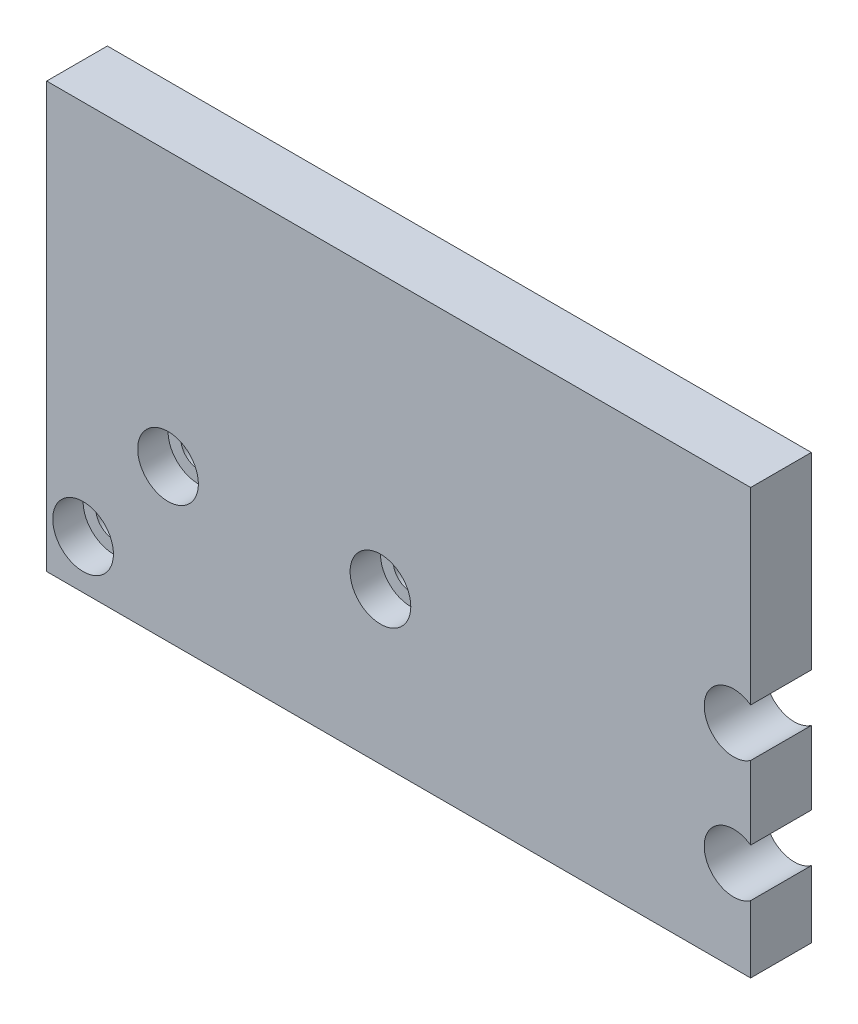
SolidWorks part; units mm, degrees
material "SKD11淬火HRC56-60"
ref_plane "前基準面" through (0, 0, 0) normal (0, 0, 1) x (1, 0, 0)
ref_plane "上基準面" through (0, 0, 0) normal (0, 1, 0) x (1, 0, 0)
ref_plane "右基準面" through (0, 0, 0) normal (1, 0, 0) x (0, 0, -1)
sketch "草图1" plane through (0, 0, 0) normal (0, 0, 1) x (1, 0, 0)
  line L1 (0, 0) -> (116, 0)
  line L2 (0, 0) -> (0, 70)
  line L3 (0, 70) -> (116, 70)
  line L4 (116, 0) -> (116, 70)
  dimension "D1" = 116
  dimension "D2" = 70
extrude "凸台-拉伸1" add sketch "草图1" along normal blind 10
sketch "草图2" plane through (0, 0, 10) normal (0, 0, 1) x (1, 0, 0)
  line L0 (0, 0) -> (116, 0) construction
  line L1 (116, 0) -> (116, 70) construction
  circle A0 centre (113.2, 35) radius 4.85
  circle A1 centre (113.2, 15) radius 4.85
  dimension "D1" = 15
  dimension "D2" = 9.7
  dimension "D3" = 20
  dimension "D4" = 2.8
extrude "切除-拉伸1" cut sketch "草图2" against normal through all
hole_wizard "M5 六角凹头螺钉的柱形沉头孔1" positions "草图5" profile "草图4" counterbore size "M5" standard "ISO" end condition through all
sketch "草图5" plane through (0, 0, 10) normal (0, 0, 1) x (1, 0, 0)
  line L0 (0, 0) -> (116, 0) construction
  line L1 (0, 70) -> (0, 0) construction
  point P0 (6, 8)
  point P1 (20, 25)
  point P3 (55, 25)
  dimension "D1" = 8
  dimension "D2" = 6
  dimension "D3" = 35
  dimension "D4" = 20
  dimension "D5" = 25
sketch "草图4" plane through (6, 8, 10) normal (1, 0, 0) x (0, -1, 0)
  line L0 (0, 0) -> (0, 10)
  line L1 (0, 10) -> (2.9, 10)
  line L3 (2.9, 10) -> (2.9, 5)
  line L4 (2.9, 5) -> (5, 5)
  line L5 (5, 5) -> (5, 0)
  line L7 (5, 0) -> (0, 0)
  line L11 (0, -6.35) -> (0, 107.95) construction
  dimension "通孔孔直径" = 5.8
  dimension "通孔孔深度" = 10
  dimension "柱形沉头孔直径" = 10
  dimension "柱形沉头孔深度" = 5
